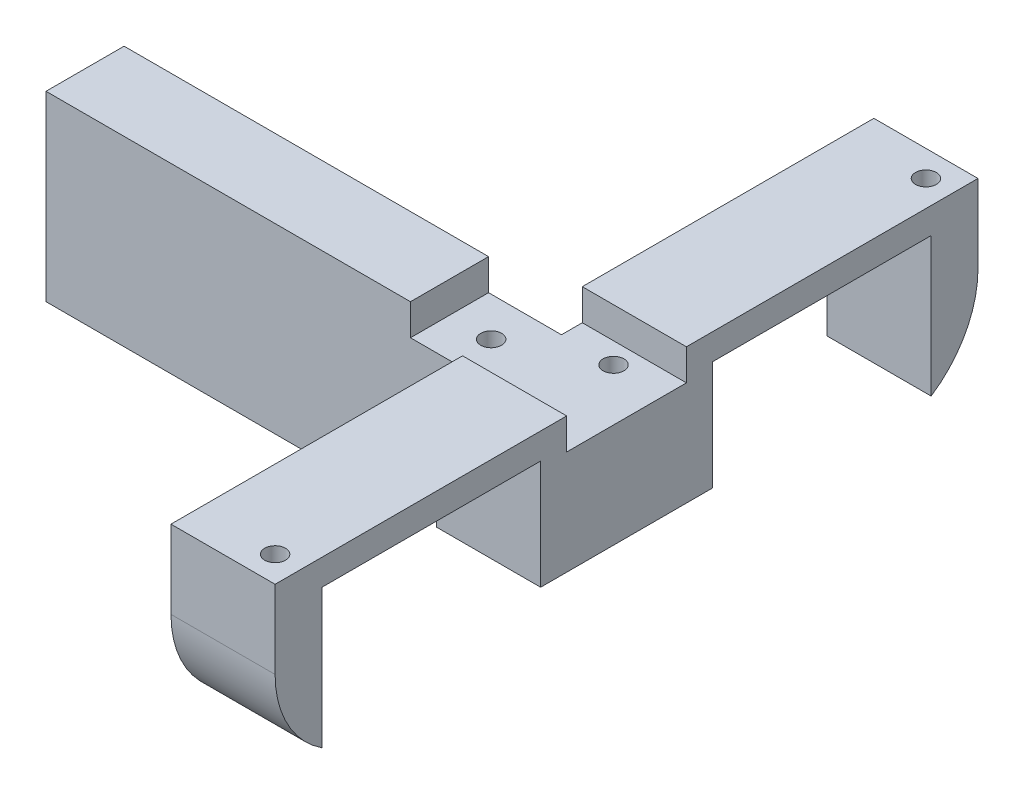
SolidWorks part; units mm, degrees
material "ABS"
ref_plane "Front Plane" through (0, 0, 0) normal (0, 0, 1) x (1, 0, 0)
ref_plane "Top Plane" through (0, 0, 0) normal (0, 1, 0) x (1, 0, 0)
ref_plane "Right Plane" through (0, 0, 0) normal (1, 0, 0) x (0, 0, -1)
sketch "Sketch1" plane through (0, 0, 0) normal (0, 1, 0) x (1, 0, 0)
  line L1 (-38.3176, 43.2333) -> (45.6824, 43.2333)
  line L2 (45.6824, 43.2333) -> (45.6824, -16.7667)
  line L3 (45.6824, -16.7667) -> (65.6824, -16.7667)
  line L4 (65.6824, -16.7667) -> (65.6824, 118.2333)
  line L7 (-38.3176, 43.2333) -> (-38.3176, 58.2333)
  line L8 (-38.3176, 58.2333) -> (45.6824, 58.2333)
  line L9 (45.6824, 58.2333) -> (45.6824, 118.2333)
  line L10 (45.6824, 118.2333) -> (65.6824, 118.2333)
  dimension "D1" = 20
  dimension "D2" = 60
  dimension "D3" = 84
  dimension "D4" = 15
  dimension "D5" = 60
  dimension "D6" = 20
extrude "Boss-Extrude1" add sketch "Sketch1" along normal blind 35
sketch "Sketch2" plane through (65.6824, 0, 0) normal (1, 0, 0) x (0, 0, -1)
  line L1 (-7.7667, 30) -> (34.2333, 30)
  line L2 (-7.7667, 30) -> (-7.7667, 9)
  line L3 (-7.7667, 9) -> (34.2333, 9)
  line L4 (34.2333, 30) -> (34.2333, 9)
  line L5 (-16.7667, 35) -> (-16.7667, 0) construction
  line L6 (50.7333, 24.6294) -> (50.7333, 59.3446) construction
  line L7 (-16.7667, 0) -> (118.2333, 0) construction
  line L9 (109.2333, 9) -> (67.2333, 9)
  line L10 (109.2333, 30) -> (109.2333, 9)
  line L11 (109.2333, 30) -> (67.2333, 30)
  line L12 (67.2333, 30) -> (67.2333, 9)
  dimension "D1" = 21
  dimension "D2" = 42
  dimension "D3" = 9
  dimension "D4" = 9
  dimension "D5" = 7.5
extrude "Cut-Extrude1" cut sketch "Sketch2" against normal up to next
sketch "Sketch3" plane through (45.6824, 0, 0) normal (-1, 0, 0) x (0, 0, 1)
  line L0 (7.7667, 9) -> (7.7667, 30) construction
  line L1 (-34.2333, 9) -> (7.7667, 9) construction
  line L2 (-50.7333, 32.1987) -> (-50.7333, 60.1119) construction
  line L3 (-43.2333, 35) -> (-43.2333, 0) construction
  circle A0 centre (11.2667, 24.75) radius 2
  circle A1 centre (11.2667, 15.25) radius 2
  circle A2 centre (-37.7333, 24.75) radius 2
  circle A3 centre (-37.7333, 15.25) radius 2
  circle A4 centre (-112.7333, 24.75) radius 2
  circle A5 centre (-112.7333, 15.25) radius 2
  circle A6 centre (-63.7333, 15.25) radius 2
  circle A7 centre (-63.7333, 24.75) radius 2
  dimension "D1" = 4
  dimension "D2" = 49
  dimension "D3" = 9.5
  dimension "D4" = 3.5
  dimension "D5" = 6.25
  dimension "D6" = 7.5
extrude "Cut-Extrude2" cut sketch "Sketch3" against normal blind 10
fillet "Fillet1" radius 20 2 edges at (55.6824, 0, 16.7667) (55.6824, 0, -118.2333)
sketch "Sketch6" plane through (65.6824, 0, 0) normal (1, 0, 0) x (0, 0, -1)
  line L0 (34.2333, 9) -> (34.2333, 30) construction
  line L1 (-7.7667, 9) -> (34.2333, 9)
  line L2 (-7.7667, 9) -> (-7.7667, 0)
  line L3 (-7.7667, 0) -> (34.2333, 0)
  line L4 (34.2333, 9) -> (34.2333, 0)
  line L5 (3.2333, 0) -> (98.2333, 0) construction
  line L6 (50.7333, 24.0053) -> (50.7333, 51.0852) construction
  line L7 (67.2333, 9) -> (67.2333, 0)
  line L8 (109.2333, 9) -> (67.2333, 9)
  line L9 (109.2333, 0) -> (67.2333, 0)
  line L10 (109.2333, 9) -> (109.2333, 0)
  dimension "D1" = 7.5
extrude "Cut-Extrude5" cut sketch "Sketch6" against normal up to next
sketch "Sketch7" plane through (-38.3176, 0, 0) normal (-1, 0, 0) x (0, 0, 1)
  line L2 (-58.2333, 35) -> (-43.2333, 35) construction
  line L3 (-43.2333, 35) -> (-43.2333, 0) construction
  circle A0 centre (-50.7333, 25) radius 2
  circle A1 centre (-50.7333, 10) radius 2
  dimension "D1" = 4
  dimension "D3" = 15
  dimension "D4" = 10
  dimension "D5" = 7.5
extrude "Cut-Extrude6" cut sketch "Sketch7" against normal blind 10
sketch "Sketch8" plane through (0, 0, 0) normal (0, -1, 0) x (1, 0, 0)
  line L1 (45.6824, -67.2333) -> (45.6824, -58.2333) construction
  line L2 (45.6824, -67.2333) -> (65.6824, -67.2333) construction
  line L3 (65.6824, -34.2333) -> (65.6824, -67.2333) construction
  line L4 (45.6824, -34.2333) -> (65.6824, -34.2333) construction
  line L5 (45.6824, -43.2333) -> (45.6824, -34.2333) construction
  line L9 (45.6824, -67.2333) -> (45.6824, -58.2333)
  line L10 (45.6824, -67.2333) -> (65.6824, -67.2333)
  line L11 (65.6824, -34.2333) -> (65.6824, -67.2333)
  line L12 (45.6824, -34.2333) -> (65.6824, -34.2333)
  line L13 (45.6824, -43.2333) -> (45.6824, -34.2333)
  line L16 (45.6824, -43.2333) -> (25.6824, -43.2333)
  line L17 (-38.3176, -43.2333) -> (45.6824, -43.2333) construction
  line L18 (25.6824, -43.2333) -> (25.6824, -58.2333)
  line L19 (45.6824, -58.2333) -> (-38.3176, -58.2333) construction
  line L20 (25.6824, -58.2333) -> (45.6824, -58.2333)
  dimension "D1" = 20
extrude "Cut-Extrude7" cut sketch "Sketch8" against normal blind 9
sketch "Sketch9" plane through (0, 9, 0) normal (0, -1, 0) x (1, 0, 0)
  line L0 (25.6824, -58.2333) -> (45.6824, -58.2333) construction
  line L1 (65.6824, -34.2333) -> (45.6824, -34.2333) construction
  line L2 (65.6824, -67.2333) -> (65.6824, -34.2333) construction
  line L3 (45.6824, -67.2333) -> (65.6824, -67.2333) construction
  circle A0 centre (55.6824, -42.2333) radius 2
  circle A1 centre (55.6824, -59.2333) radius 2
  circle A2 centre (35.6824, -50.7333) radius 2
  dimension "D1" = 4
  dimension "D2" = 7.5
  dimension "D3" = 30
  dimension "D4" = 10
  dimension "D5" = 8
  dimension "D6" = 8
extrude "Cut-Extrude8" cut sketch "Sketch9" against normal blind 10
sketch "Sketch10" plane through (0, 35, 0) normal (0, 1, 0) x (1, 0, 0)
  line L0 (45.6824, 62.2333) -> (65.6824, 62.2333)
  line L1 (45.6824, 118.2333) -> (45.6824, 58.2333) construction
  line L2 (65.6824, -16.7667) -> (65.6824, 118.2333) construction
  line L3 (65.6824, 62.2333) -> (65.6824, 39.2333)
  line L4 (65.6824, 39.2333) -> (45.6824, 39.2333)
  line L5 (45.6824, 43.2333) -> (45.6824, -16.7667) construction
  line L7 (45.6824, 39.2333) -> (45.6824, 43.2333)
  line L8 (45.6824, 43.2333) -> (31.6824, 43.2333)
  line L9 (-38.3176, 43.2333) -> (45.6824, 43.2333) construction
  line L10 (31.6824, 43.2333) -> (31.6824, 58.2333)
  line L11 (45.6824, 58.2333) -> (-38.3176, 58.2333) construction
  line L12 (31.6824, 58.2333) -> (45.6824, 58.2333)
  line L13 (45.6824, 58.2333) -> (45.6824, 62.2333)
  dimension "D1" = 5
  dimension "D2" = 5
  dimension "D3" = 14
extrude "Cut-Extrude9" cut sketch "Sketch10" against normal blind 6
sketch "Sketch11" plane through (0, 29, 0) normal (0, 1, 0) x (1, 0, 0)
  line L0 (45.6824, 62.2333) -> (45.6824, 58.2333) construction
  line L1 (45.6824, 58.2333) -> (31.6824, 58.2333) construction
  circle A0 centre (55.6824, 58.2333) radius 2
  circle A1 centre (55.6824, 43.2333) radius 2
  circle A2 centre (39.6824, 50.7333) radius 2
  dimension "D1" = 4
  dimension "D2" = 10
  dimension "D3" = 7.5
  dimension "D4" = 6
  dimension "D5" = 0
extrude "Cut-Extrude10" cut sketch "Sketch11" against normal blind 9
sketch "Sketch12" plane through (0, 35, 0) normal (0, 1, 0) x (1, 0, 0)
  line L0 (65.6824, 118.2333) -> (45.6824, 118.2333) construction
  line L1 (45.6824, -16.7667) -> (65.6824, -16.7667) construction
  line L2 (65.6824, -16.7667) -> (65.6824, 39.2333) construction
  line L3 (65.6824, 62.2333) -> (65.6824, 118.2333) construction
  circle A0 centre (60.6824, -11.7667) radius 2
  circle A1 centre (60.6824, 113.2333) radius 2
  dimension "D2" = 4
  dimension "D1" = 5
  dimension "D3" = 5
  dimension "D4" = 5
  dimension "D5" = 5
extrude "Cut-Extrude11" cut sketch "Sketch12" against normal blind 10
